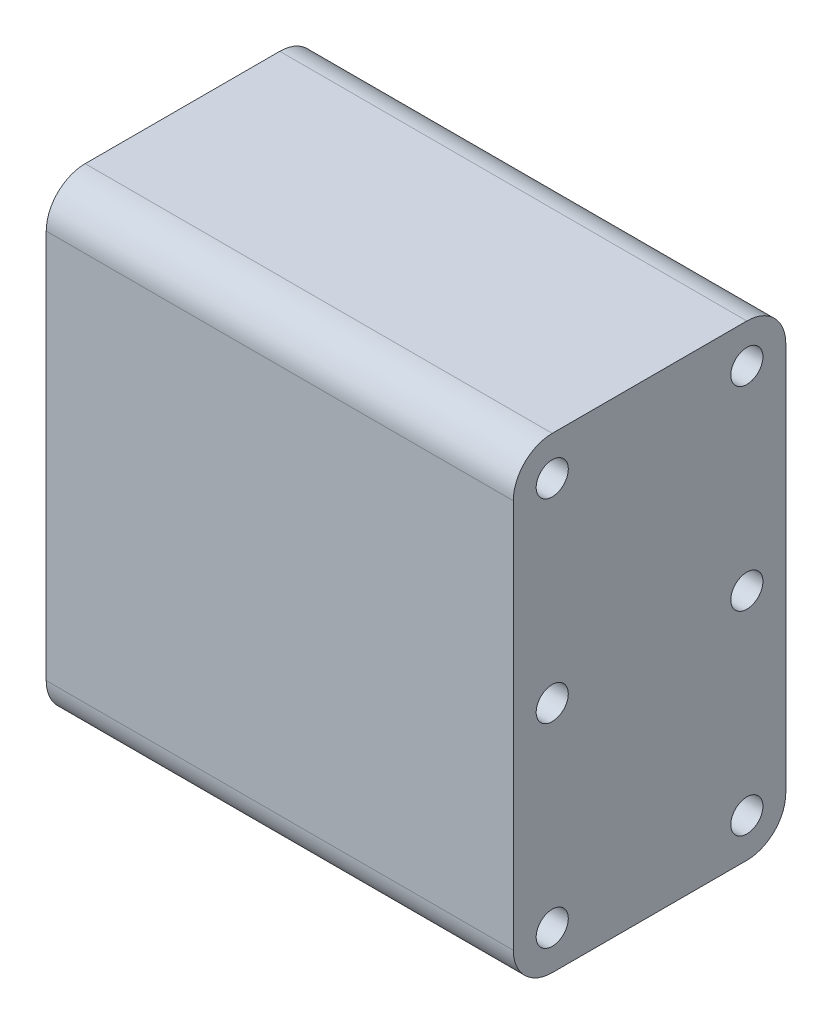
SolidWorks part; units mm, degrees
ref_plane "前视基准面" through (0, 0, 0) normal (0, 0, 1) x (1, 0, 0)
ref_plane "上视基准面" through (0, 0, 0) normal (0, 1, 0) x (1, 0, 0)
ref_plane "右视基准面" through (0, 0, 0) normal (1, 0, 0) x (0, 0, -1)
sketch "草图1" plane through (0, 0, 0) normal (1, 0, 0) x (0, 0, -1)
  line L3 (13, -3.0752) -> (13, -7.0752)
  line L4 (13, -7.0752) -> (17, -7.0752)
  line L5 (7, -3.0752) -> (7, -7.0752)
  line L6 (7, -7.0752) -> (3, -7.0752)
  line L7 (3, -13.0752) -> (7, -13.0752)
  line L8 (7, -13.0752) -> (7, -17.0752)
  line L9 (13, -17.0752) -> (13, -13.0752)
  line L10 (13, -13.0752) -> (17, -13.0752)
  circle A0 centre (10, -3.0752) radius 1.7
  circle A1 centre (3, -10.0752) radius 1.65
  circle A2 centre (10, -17.0752) radius 1.7
  circle A3 centre (17, -10.0752) radius 1.7
  circle A4 centre (10, -10.0752) radius 1.7
  arc A6 (3, -7.0752) -> (3, -13.0752) centre (3, -10.0752) ccw
  arc A7 (17, -7.0752) -> (17, -13.0752) centre (17, -10.0752) cw
  arc A8 (7, -3.0752) -> (13, -3.0752) centre (10, -3.0752) cw
  arc A9 (7, -17.0752) -> (13, -17.0752) centre (10, -17.0752) ccw
  dimension "D3" = 3.4
  dimension "D4" = 3.3
  dimension "D5" = 3.4
  dimension "D6" = 3.4
  dimension "D7" = 3.4
  dimension "D2" = 7
  dimension "D8" = 7
  dimension "D9" = 7
  dimension "D11" = 7
extrude "凸台-拉伸1" add sketch "草图1" along normal blind 3
sketch "草图2" plane through (3, 0, 0) normal (1, 0, 0) x (0, 0, -1)
  line L2 (-4, 3.9248) -> (-4, -44.0752)
  line L3 (-4, 3.9248) -> (24, 3.9248)
  line L4 (-4, -44.0752) -> (24, -44.0752)
  line L5 (24, -44.0752) -> (24, 3.9248)
  dimension "D3" = 48
  dimension "D4" = 28
extrude "凸台-拉伸2" add sketch "草图2" along normal blind 48
fillet "圆角1" radius 4 4 edges at (27, -44.0752, -24) (27, -44.0752, 4) (27, 3.9248, 4) (27, 3.9248, -24)
sketch "草图3" plane through (3, 0, 0) normal (-1, 0, 0) x (0, 0, 1)
  line L0 (-24, -40.0752) -> (-24, -0.0752) construction
  line L1 (-20, 3.9248) -> (0, 3.9248) construction
  line L2 (4, -0.0752) -> (4, -40.0752) construction
  line L3 (0, -44.0752) -> (-20, -44.0752) construction
  circle A0 centre (-20, -0.0752) radius 1.65
  circle A1 centre (0, -0.0752) radius 1.65
  circle A2 centre (0, -20.0752) radius 1.65
  circle A3 centre (-20, -20.0752) radius 1.65
  circle A4 centre (-20, -40.0752) radius 1.65
  circle A5 centre (0, -40.0752) radius 1.65
  point P21 (-24, -20.0752)
  point P23 (4, -20.0752)
  dimension "D1" = 3.3
  dimension "D2" = 3.3
  dimension "D3" = 3.3
  dimension "D4" = 3.3
  dimension "D5" = 3.3
  dimension "D6" = 3.3
  dimension "D17" = 20
  dimension "D7" = 4
  dimension "D8" = 4
  dimension "D9" = 4
  dimension "D10" = 4
  dimension "D11" = 4
  dimension "D12" = 4
  dimension "D13" = 4
  dimension "D14" = 4
  dimension "D15" = 4
  dimension "D16" = 4
extrude "切除-拉伸1" cut sketch "草图3" against normal blind 4
sketch "草图4" plane through (51, 0, 0) normal (1, 0, 0) x (0, 0, -1)
  line L0 (-4, -0.0752) -> (-4, -40.0752) construction
  line L3 (20, 3.9248) -> (0, 3.9248) construction
  line L4 (24, -40.0752) -> (24, -0.0752) construction
  line L5 (0, -44.0752) -> (20, -44.0752) construction
  circle A0 centre (0, -0.0752) radius 1.65
  circle A1 centre (20, -0.0752) radius 1.65
  circle A2 centre (0, -20.0752) radius 1.65
  circle A3 centre (20, -20.0752) radius 1.65
  circle A4 centre (0, -40.0752) radius 1.65
  circle A5 centre (20, -40.0752) radius 1.65
  point P21 (24, -20.0752)
  point P24 (-4, -20.0752)
  dimension "D1" = 3.3
  dimension "D2" = 3.3
  dimension "D3" = 3.3
  dimension "D4" = 3.3
  dimension "D5" = 3.3
  dimension "D6" = 3.3
  dimension "D7" = 4
  dimension "D8" = 4
  dimension "D9" = 4
  dimension "D10" = 4
  dimension "D11" = 4
  dimension "D12" = 4
  dimension "D13" = 4
  dimension "D14" = 4
  dimension "D15" = 4
  dimension "D16" = 4
extrude "切除-拉伸2" cut sketch "草图4" against normal blind 4
fillet "圆角2" radius 2 4 edges at (1.5, -13.0752, -13) (1.5, -13.0752, -7) (1.5, -7.0752, -7) (1.5, -7.0752, -13)
